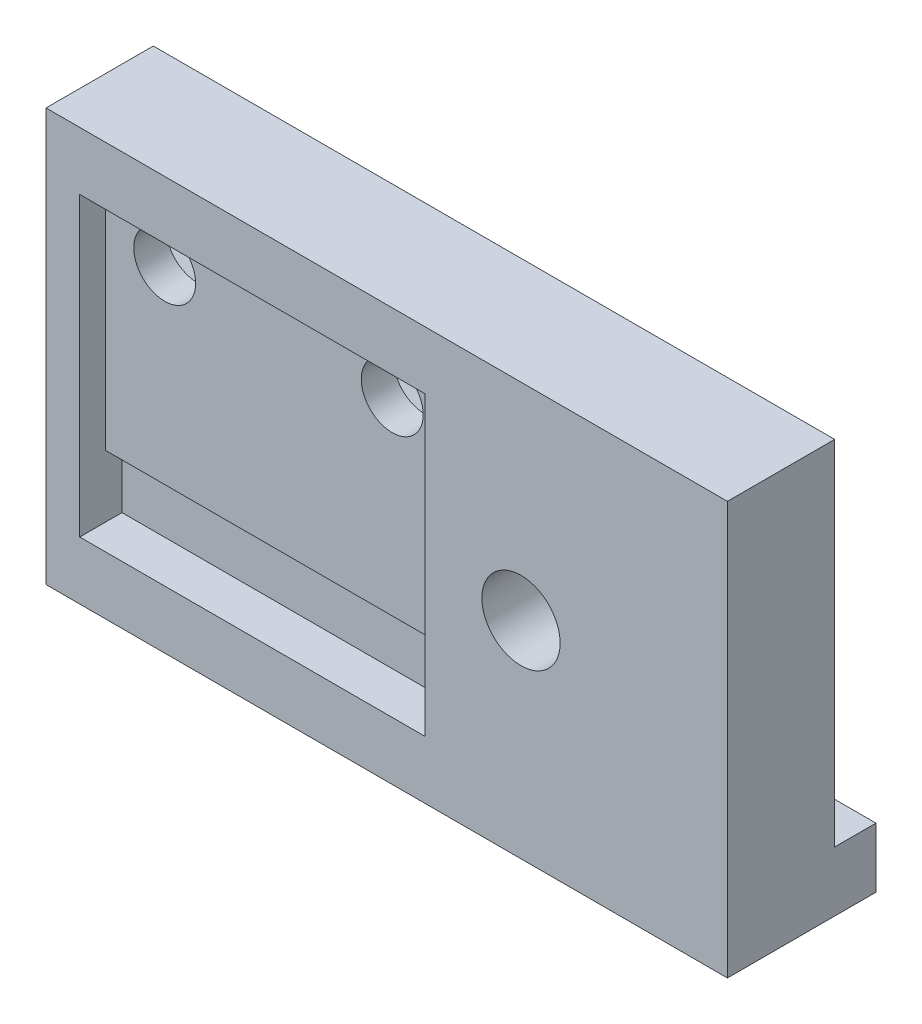
SolidWorks part; units mm, degrees
ref_plane "Front Plane" through (0, 0, 0) normal (0, 0, 1) x (1, 0, 0)
ref_plane "Top Plane" through (0, 0, 0) normal (0, 1, 0) x (1, 0, 0)
ref_plane "Right Plane" through (0, 0, 0) normal (1, 0, 0) x (0, 0, -1)
sketch "Sketch1" plane through (0, 0, 0) normal (0, 0, 1) x (1, 0, 0)
  line L0 (19.7, 12.7) -> (29.225, 12.7) construction
  line L1 (0, 0) -> (41.925, 0)
  line L2 (0, 0) -> (0, 25.4)
  line L3 (0, 25.4) -> (41.925, 25.4)
  line L4 (41.925, 0) -> (41.925, 25.4)
  line L5 (5.7, 19.05) -> (19.7, 19.05) construction
  line L6 (5.7, 19.05) -> (5.7, 6.35) construction
  line L7 (5.7, 6.35) -> (19.7, 6.35) construction
  line L8 (19.7, 19.05) -> (19.7, 6.35) construction
  line L9 (12.7, 19.05) -> (12.7, 25.4) construction
  line L10 (12.7, 6.35) -> (12.7, 0) construction
  line L11 (1.27, 24.13) -> (1.27, 25.4) construction
  line L12 (24.13, 1.27) -> (1.27, 1.27) construction
  line L13 (24.13, 1.27) -> (24.13, 24.13) construction
  line L14 (24.13, 24.13) -> (1.27, 24.13) construction
  line L15 (1.27, 1.27) -> (1.27, 24.13) construction
  line L16 (24.13, 1.27) -> (1.27, 24.13) construction
  line L17 (24.13, 24.13) -> (1.27, 1.27) construction
  line L18 (1.27, 24.13) -> (0, 24.13) construction
  circle A0 centre (5.7, 19.05) radius 1.904
  circle A1 centre (19.7, 19.05) radius 1.904
  circle A2 centre (19.7, 6.35) radius 1.904 construction
  circle A3 centre (5.7, 6.35) radius 1.904 construction
  circle A4 centre (29.225, 12.7) radius 2.4067
  point P20 (12.7, 12.7)
  dimension "D1" = 4.8133
  dimension "D2" = 3.808
  dimension "D3" = 12.7
  dimension "D4" = 14
  dimension "D5" = 25.4
  dimension "D6" = 22.86
  dimension "D7" = 1.27
  dimension "D8" = 9.525
  dimension "D9" = 12.7
extrude "Boss-Extrude1" add sketch "Sketch1" along normal blind 2
sketch "Sketch2" plane through (0, 0, 2) normal (0, 0, 1) x (1, 0, 0)
  line L0 (5.7, 19.05) -> (19.7, 19.05) construction
  line L1 (12.7, 19.05) -> (12.7, 12.7) construction
  line L3 (2.073, 3.573) -> (23.327, 3.573)
  line L4 (0, 25.4) -> (0, 0)
  line L5 (0, 0) -> (41.925, 0)
  line L6 (41.925, 0) -> (41.925, 25.4)
  line L7 (41.925, 25.4) -> (0, 25.4)
  line L8 (0, 25.4) -> (0, 0)
  line L9 (0, 0) -> (41.925, 0)
  line L10 (41.925, 0) -> (41.925, 25.4)
  line L11 (41.925, 25.4) -> (0, 25.4)
  line L12 (2.073, 3.573) -> (2.073, 21.827)
  line L13 (2.073, 21.827) -> (23.327, 21.827)
  line L14 (23.327, 3.573) -> (23.327, 21.827)
  line L15 (2.073, 3.573) -> (23.327, 21.827) construction
  line L16 (2.073, 21.827) -> (23.327, 3.573) construction
  circle A0 centre (29.225, 12.7) radius 2.4067 construction
  circle A1 centre (29.225, 12.7) radius 2.4067
  point P12 (12.7, 12.7)
  point P13 (12.7, 12.7)
  point P21 (0, 0)
  dimension "D2" = 21.254
  dimension "D3" = 18.254
  dimension "D1" = 0
extrude "Boss-Extrude2" add sketch "Sketch2" along normal blind 1.6
sketch "Sketch3" plane through (0, 0, 0) normal (0, 0, -1) x (-1, 0, 0)
  line L1 (-16.569, 17.2423) -> (-16.569, 20.8577)
  line L2 (-16.569, 20.8577) -> (-19.7, 22.6654)
  line L3 (-19.7, 22.6654) -> (-22.831, 20.8577)
  line L4 (0, 0) -> (0, 25.4)
  line L5 (0, 25.4) -> (-41.925, 25.4)
  line L6 (-41.925, 25.4) -> (-41.925, 0)
  line L7 (-41.925, 0) -> (0, 0)
  line L8 (0, 0) -> (0, 25.4)
  line L9 (0, 25.4) -> (-41.925, 25.4)
  line L10 (-41.925, 25.4) -> (-41.925, 0)
  line L11 (-41.925, 0) -> (0, 0)
  line L12 (-22.831, 20.8577) -> (-22.831, 17.2423)
  line L13 (-22.831, 17.2423) -> (-19.7, 15.4346)
  line L14 (-19.7, 15.4346) -> (-16.569, 17.2423)
  line L15 (-2.569, 20.8577) -> (-5.7, 22.6654)
  line L16 (-5.7, 22.6654) -> (-8.831, 20.8577)
  line L17 (-8.831, 20.8577) -> (-8.831, 17.2423)
  line L18 (-8.831, 17.2423) -> (-5.7, 15.4346)
  line L19 (-5.7, 15.4346) -> (-2.569, 17.2423)
  line L20 (-2.569, 17.2423) -> (-2.569, 20.8577)
  circle A0 centre (-29.225, 12.7) radius 2.4067 construction
  circle A1 centre (-29.225, 12.7) radius 2.4067
  circle A2 centre (-19.7, 19.05) radius 3.131 construction
  circle A3 centre (-5.7, 19.05) radius 3.131 construction
  circle A6 centre (-5.7, 19.05) radius 1.904 construction
  dimension "D2" = 6.262
  dimension "D1" = 0
extrude "Boss-Extrude3" add sketch "Sketch3" along normal blind 3
sketch "Sketch4" plane through (0, 0, -3) normal (0, 0, -1) x (-1, 0, 0)
  line L4 (-41.925, 3.683) -> (-41.925, 0)
  line L5 (-41.925, 0) -> (0, 0)
  line L6 (-41.925, 0) -> (0, 0) construction
  line L7 (0, 0) -> (0, 3.683)
  line L8 (0, 3.683) -> (-41.925, 3.683)
  line L10 (0, 0) -> (0, 25.4) construction
  line L11 (-41.925, 25.4) -> (-41.925, 0) construction
  line L12 (-31.115, 12.7) -> (49968.885, 12.7) construction
  circle A2 centre (-29.225, 12.7) radius 2.4067 construction
  point P0 (-29.225, 12.7)
  dimension "D1" = 18.034
extrude "Boss-Extrude4" add sketch "Sketch4" along normal blind 2.54
sketch "Sketch5" plane through (0, 0, 2) normal (0, 0, 1) x (1, 0, 0)
  line L0 (2.073, 21.827) -> (2.073, 3.573) construction
  line L1 (2.073, 7.383) -> (23.327, 7.383)
  line L2 (2.073, 7.383) -> (2.073, 3.573)
  line L3 (2.073, 3.573) -> (23.327, 3.573)
  line L4 (23.327, 7.383) -> (23.327, 3.573)
  dimension "D1" = 3.81
extrude "Cut-Extrude1" cut sketch "Sketch5" against normal blind 1
